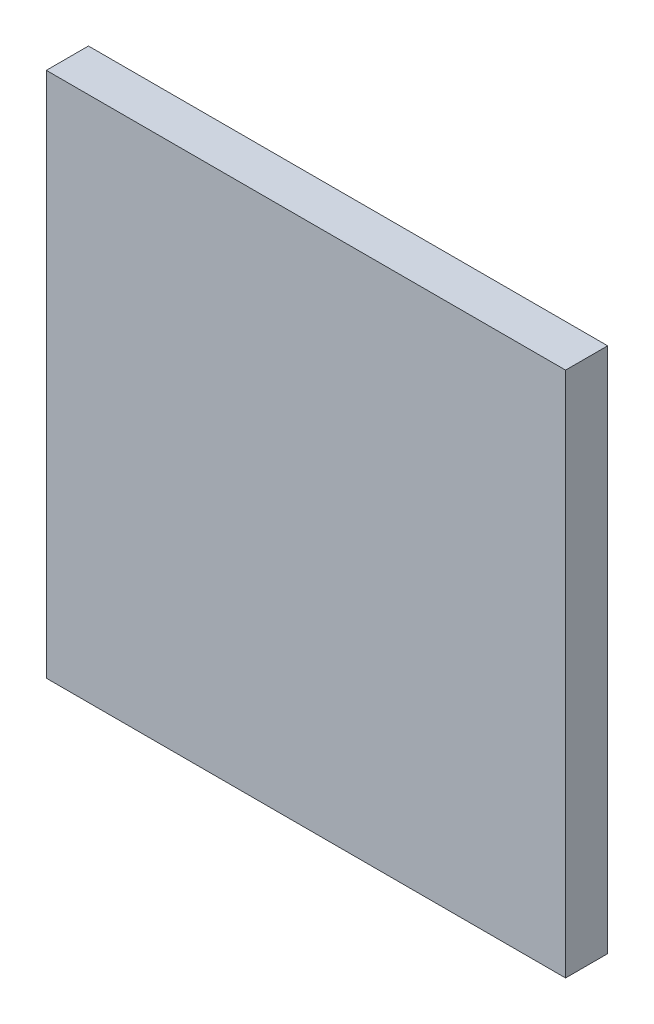
SolidWorks part; units mm, degrees
ref_plane "Plano frontal" through (0, 0, 0) normal (0, 0, 1) x (1, 0, 0)
ref_plane "Plano superior" through (0, 0, 0) normal (0, 1, 0) x (1, 0, 0)
ref_plane "Plano direito" through (0, 0, 0) normal (1, 0, 0) x (0, 0, -1)
sketch "Esboço1" plane through (0, 0, 0) normal (0, 0, 1) x (1, 0, 0)
  line L0 (0, 0) -> (123.29, 0)
  line L1 (0, 0) -> (0, 125)
  line L2 (123.29, 0) -> (123.29, 125)
  line L3 (123.29, 125) -> (0, 125)
  point P5 (0, 0)
  dimension "D1" = 123.29
  dimension "D2" = 125
extrude "Ressalto-extrusão1" add sketch "Esboço1" along normal blind 10
sketch "Esboço2" plane through (0, 0, 10) normal (0, 0, 1) x (1, 0, 0)
  line L1 (123.29, 125) -> (0, 125)
